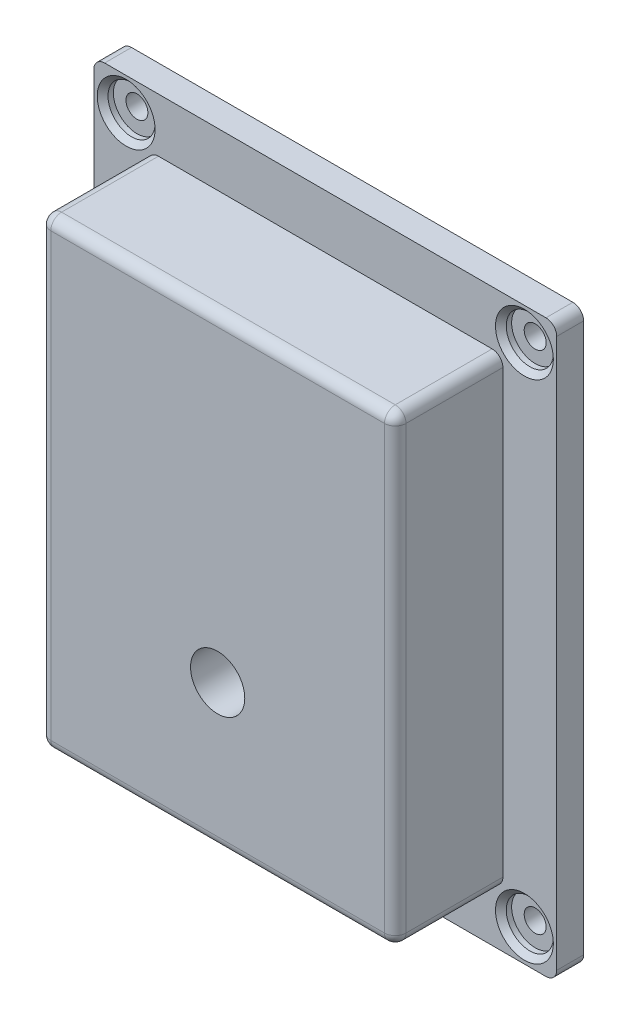
SolidWorks part; units mm, degrees
ref_plane "Front Plane" through (0, 0, 0) normal (1, 0, 0) x (0, 1, 0)
ref_plane "Top Plane" through (0, 0, 0) normal (0, 0, 1) x (0, 1, 0)
ref_plane "Right Plane" through (0, 0, 0) normal (0, 1, 0) x (-1, 0, 0)
sketch "Sketch2" plane through (0, 0, 0) normal (0, 0, 1) x (0, 1, 0)
  line L1 (0, 0) -> (41.91, 0)
  line L2 (0, 0) -> (0, 29.21)
  line L3 (0, 29.21) -> (41.91, 29.21)
  line L4 (41.91, 0) -> (41.91, 29.21)
  line L5 (-6.35, -6.35) -> (48.26, -6.35)
  line L6 (-6.35, -6.35) -> (-6.35, 35.56)
  line L7 (-6.35, 35.56) -> (48.26, 35.56)
  line L8 (48.26, -6.35) -> (48.26, 35.56)
  dimension "D1" = 29.21
  dimension "D2" = 41.91
  dimension "D3" = 6.35
  dimension "D4" = 6.35
  dimension "D6" = 6.35
  dimension "D5" = 6.35
extrude "Boss-Extrude1" add sketch "Sketch2" along normal blind 9.525
sketch "Sketch4" plane through (0, 0, 9.525) normal (0, 0, 1) x (1, 0, 0)
  line L1 (-35.56, 48.26) -> (6.35, 48.26)
  line L2 (-35.56, 48.26) -> (-35.56, -6.35)
  line L3 (-35.56, -6.35) -> (6.35, -6.35)
  line L4 (6.35, 48.26) -> (6.35, -6.35)
extrude "Boss-Extrude2" add sketch "Sketch4" along normal blind 6.35
sketch "Sketch6" plane through (0, 0, 15.875) normal (0, 0, 1) x (1, 0, 0)
  line L0 (6.35, 48.26) -> (-35.56, 48.26) construction
  line L2 (-35.56, -6.35) -> (6.35, -6.35) construction
  circle A0 centre (-14.605, 10.668) radius 3.2004
  point P2 (-14.605, 48.26)
  dimension "D1" = 17.018
extrude "Cut-Extrude1" cut sketch "Sketch6" against normal through all
sketch "Sketch7" plane through (0, 0, 0) normal (0, 0, 1) x (0, 1, 0)
  line L1 (-6.35, -6.35) -> (48.26, -6.35)
  line L2 (-6.35, -6.35) -> (-6.35, 35.56)
  line L3 (-6.35, 35.56) -> (48.26, 35.56)
  line L4 (48.26, -6.35) -> (48.26, 35.56)
  line L5 (-12.7, -12.7) -> (54.61, -12.7)
  line L6 (-12.7, -12.7) -> (-12.7, 41.91)
  line L7 (-12.7, 41.91) -> (54.61, 41.91)
  line L8 (54.61, -12.7) -> (54.61, 41.91)
  dimension "D3" = 6.35
  dimension "D4" = 6.35
  dimension "D1" = 6.35
  dimension "D2" = 6.35
extrude "Boss-Extrude3" add sketch "Sketch7" along normal blind 3.175
sketch "Sketch8" plane through (0, 0, 3.175) normal (0, 0, 1) x (1, 0, 0)
  line L0 (-35.56, 48.26) -> (-35.56, -6.35) construction
  line L1 (6.35, 48.26) -> (-35.56, 48.26) construction
  line L2 (6.35, -6.35) -> (6.35, 48.26) construction
  line L3 (-35.56, -6.35) -> (6.35, -6.35) construction
  point P0 (-38.1, 50.8)
  point P1 (8.89, 50.8)
  point P2 (8.89, -8.89)
  point P3 (-38.1, -8.89)
  dimension "D1" = 2.54
  dimension "D2" = 2.54
  dimension "D3" = 2.54
  dimension "D4" = 2.54
hole_wizard "CBORE for #2 Binding Head Machine Screw1" positions "Sketch8" profile "Sketch9" counterbore size "#2" standard "ANSI Inch" end condition through all
sketch "Sketch9" plane through (-38.1, 50.8, 3.175) normal (1, 0, 0) x (0, -1, 0)
  line L0 (0, 0) -> (0, 3.175)
  line L1 (0, 3.175) -> (1.2954, 3.175)
  line L3 (1.2954, 3.175) -> (1.2954, 1.27)
  line L4 (2.7788, 1.27) -> (1.2954, 1.27)
  line L5 (2.7788, 1.27) -> (2.7788, 0.635)
  line L6 (2.7788, 0.635) -> (3.4138, 0)
  line L7 (3.4138, 0) -> (0, 0)
  line L8 (-2.7788, 0.635) -> (-3.4138, 0) construction
  line L11 (0, -6.35) -> (0, 107.95) construction
  dimension "Thru Hole Dia." = 2.5908
  dimension "Thru Hole Depth" = 3.175
  dimension "C'Bore Dia." = 5.5575
  dimension "C'Bore Depth" = 1.27
  dimension "Near C'Sink Dia." = 6.8275
  dimension "Near C'Sink Angle" = 90
fillet "Fillet1" radius 1.27 12 edges at (-41.91, 54.61, 1.5875) (12.7, 54.61, 1.5875) (12.7, -12.7, 1.5875) (-41.91, -12.7, 1.5875) (6.35, 48.26, 9.525) (-35.56, 48.26, 9.525) (-14.605, 48.26, 15.875) (-35.56, 20.955, 15.875) (6.35, 20.955, 15.875) (-14.605, -6.35, 15.875) (6.35, -6.35, 9.525) (-35.56, -6.35, 9.525)
equation "\"THICKNESS_WALL\"= 0.25"
equation "\"D3@Sketch2\"=\"THICKNESS_WALL\""
equation "\"D4@Sketch2\"=\"THICKNESS_WALL\""
equation "\"D6@Sketch2\"=\"THICKNESS_WALL\""
equation "\"D5@Sketch2\"=\"THICKNESS_WALL\""
equation "\"MAX_GEAR_HEIGHT\"= 0.375"
equation "\"D1@Boss-Extrude1\"=\"MAX_GEAR_HEIGHT\""
equation "\"D1@Boss-Extrude2\"=\"THICKNESS_WALL\""
equation "\"LARGE_GEAR_DIA\"= 1.042"
equation "\"CLEARANCE\" = 0.42"
equation "\"D1@Sketch7\"=\"THICKNESS_WALL\""
equation "\"D2@Sketch7\"=\"THICKNESS_WALL\""
equation "\"D3@Sketch7\"=\"THICKNESS_WALL\""
equation "\"D4@Sketch7\"=\"THICKNESS_WALL\""
equation "\"D1@Boss-Extrude3\"=\"CLEARANCE\""
equation "\"D1@Sketch8\"=\"THICKNESS_WALL\"/2.5"
equation "\"D2@Sketch8\"=\"THICKNESS_WALL\"/2.5"
equation "\"D3@Sketch8\"=\"THICKNESS_WALL\"/2.5"
equation "\"D4@Sketch8\"=\"THICKNESS_WALL\"/2.5"
equation "\"LARGE_BEARING_DIA\"=0.376"
equation "\"D2@Sketch6\"=\"SMALL_BEARING_DIA\""
equation "\"SMALL_GEAR_DIA\"= 0.417"
equation "\"SMALL_BEARING_DIA\"= 0.252"
equation "\"PITCH_LARGE_DIA\"= 1"
equation "\"PITCH_SMALL_DIA\"= 0.375"
equation "\"DISTANCE_BETWEEN\"= ( \"PITCH_LARGE_DIA\" + \"PITCH_SMALL_DIA\" ) / 2"
equation "\"D1@Sketch6\"=\"CLEARANCE\"+\"THICKNESS_WALL\""
